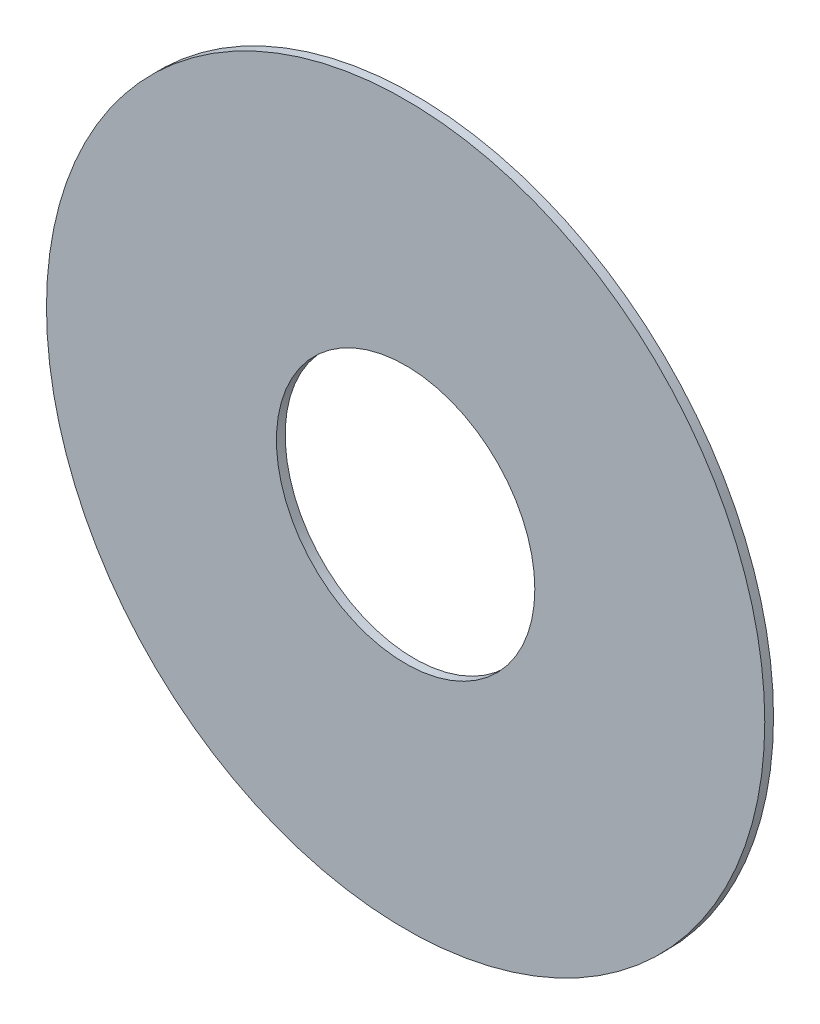
SolidWorks part; units mm, degrees
ref_plane "Спереди" through (0, 0, 0) normal (0, 0, 1) x (1, 0, 0)
ref_plane "Сверху" through (0, 0, 0) normal (0, 1, 0) x (1, 0, 0)
ref_plane "Справа" through (0, 0, 0) normal (1, 0, 0) x (0, 0, -1)
sketch "Эскиз1" plane through (0, 0, 0) normal (0, 0, 1) x (1, 0, 0)
  circle A0 centre (0, 0) radius 82
  circle A1 centre (0, 0) radius 29.5
extrude "Printed_guard" add sketch "Эскиз1" along normal blind 2 from offset 42.5
